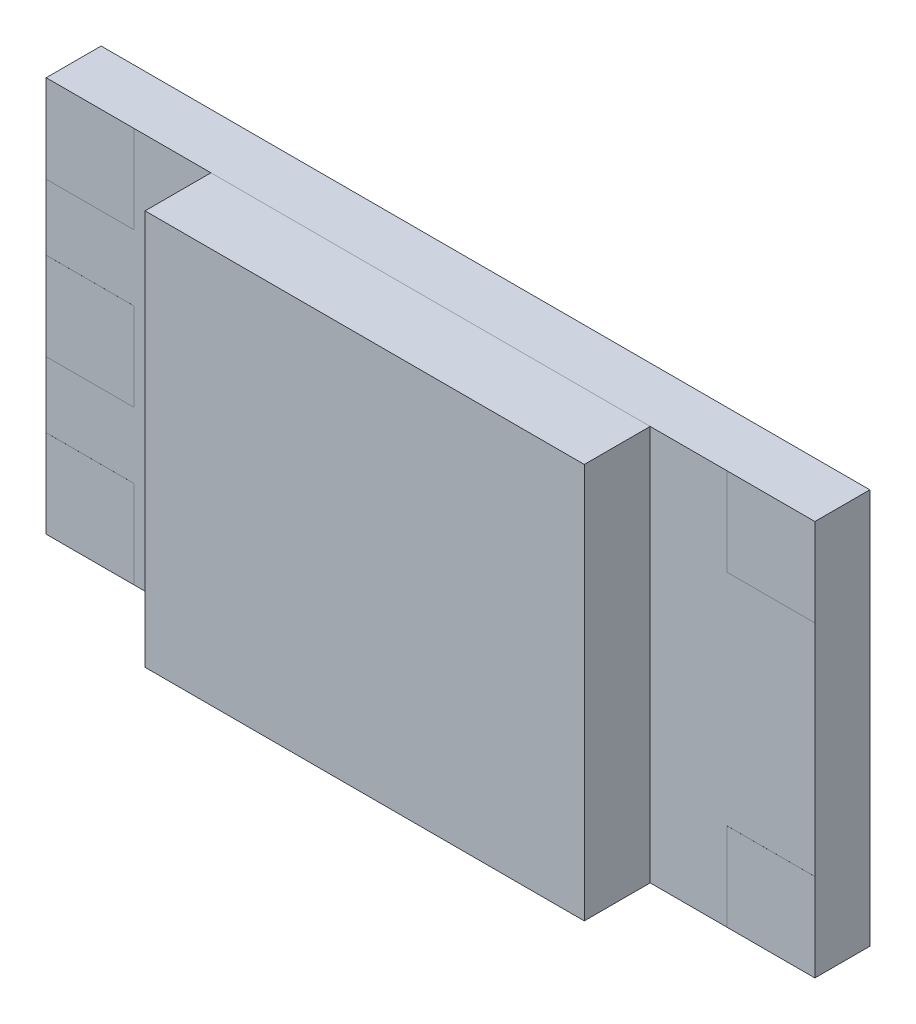
SolidWorks part; units mm, degrees
ref_plane "Front Plane" through (0, 0, 0) normal (0, 0, 1) x (1, 0, 0)
ref_plane "Top Plane" through (0, 0, 0) normal (0, 1, 0) x (1, 0, 0)
ref_plane "Right Plane" through (0, 0, 0) normal (1, 0, 0) x (0, 0, -1)
sketch "Sketch1" plane through (0, 0, 0) normal (0, 0, 1) x (1, 0, 0)
  line L1 (0, 0) -> (35, 0)
  line L2 (0, 0) -> (0, 18)
  line L3 (0, 18) -> (35, 18)
  line L4 (35, 0) -> (35, 18)
  dimension "D1" = 18
  dimension "D2" = 35
extrude "Boss-Extrude1" add sketch "Sketch1" along normal blind 2.5
sketch "Sketch2" plane through (0, 0, 2.5) normal (0, 0, 1) x (1, 0, 0)
  line L0 (35, 18) -> (0, 18) construction
  line L1 (7.5, 18) -> (27.5, 18)
  line L2 (7.5, 18) -> (7.5, 0)
  line L3 (7.5, 0) -> (27.5, 0)
  line L4 (27.5, 18) -> (27.5, 0)
  line L5 (0, 0) -> (35, 0) construction
  point P8 (17.5, 0)
  point P9 (17.5, 0)
  dimension "D1" = 20
extrude "Boss-Extrude2" add sketch "Sketch2" along normal blind 3 separate body
sketch "Sketch3" plane through (0, 0, 2.5) normal (0, 0, 1) x (1, 0, 0)
  line L0 (0, 18) -> (0, 0) construction
  line L1 (0, 18) -> (4, 18)
  line L2 (0, 18) -> (0, 14)
  line L3 (0, 14) -> (4, 14)
  line L4 (4, 18) -> (4, 14)
  line L5 (0, 11) -> (4, 11)
  line L6 (0, 11) -> (0, 7)
  line L7 (0, 7) -> (4, 7)
  line L8 (4, 11) -> (4, 7)
  line L10 (0, 0) -> (4, 0)
  line L11 (0, 0) -> (0, 4)
  line L12 (0, 4) -> (4, 4)
  line L13 (4, 0) -> (4, 4)
  line L14 (35, 18) -> (31, 18)
  line L15 (35, 18) -> (35, 14)
  line L16 (35, 14) -> (31, 14)
  line L17 (31, 18) -> (31, 14)
  line L18 (35, 0) -> (31, 0)
  line L19 (35, 0) -> (35, 4)
  line L20 (35, 4) -> (31, 4)
  line L21 (31, 0) -> (31, 4)
  point P26 (0, 9)
  point P27 (0, 9)
  dimension "D1" = 4
  dimension "D2" = 4
extrude "Boss-Extrude3" add sketch "Sketch3" along normal blind 0.001 separate body
